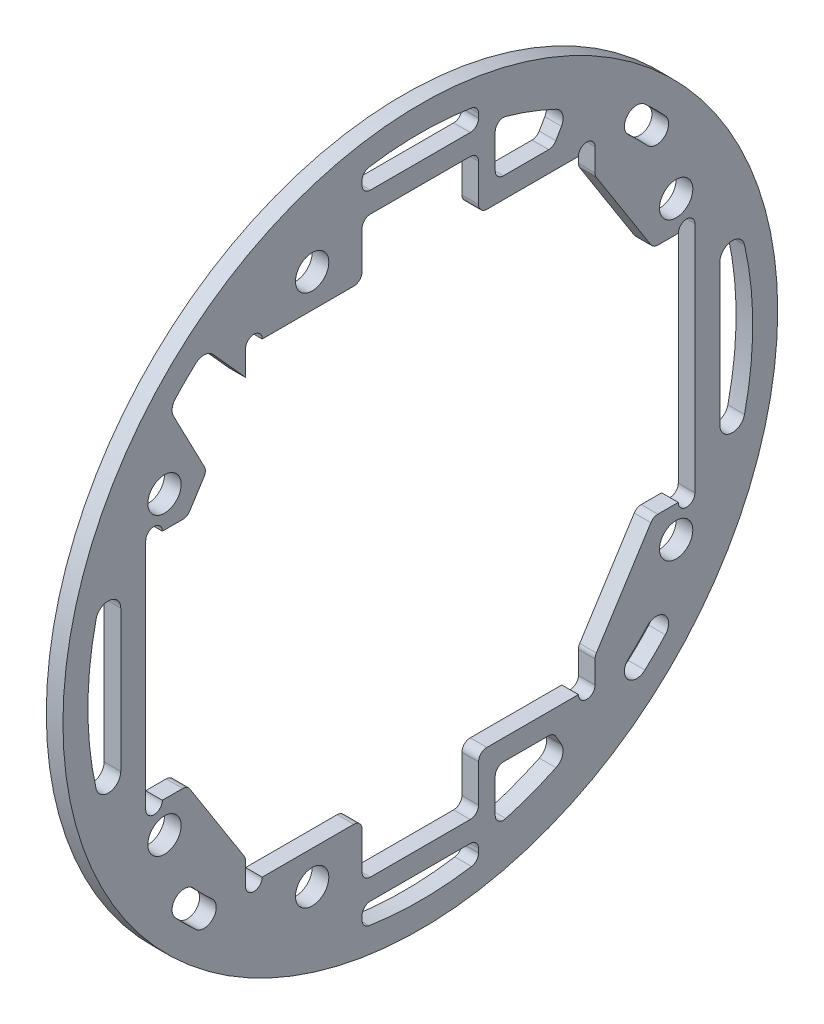
SolidWorks part; units mm, degrees
material "Thornel Mat VMA"
ref_plane "前视基准面" through (0, 0, 0) normal (0, 0, 1) x (1, 0, 0)
ref_plane "上视基准面" through (0, 0, 0) normal (0, 1, 0) x (1, 0, 0)
ref_plane "右视基准面" through (0, 0, 0) normal (1, 0, 0) x (0, 0, -1)
sketch "草图1" plane through (0, 0, 0) normal (1, 0, 0) x (0, 0, -1)
  line L25 (-21, 28) -> (21, 28)
  line L26 (-28, 14) -> (-33, 14)
  line L31 (-33, 14) -> (-33, -14)
  line L38 (1.1, 0) -> (-1.1, 0) construction
  line L48 (0, 1.1) -> (0, -1.1) construction
  line L58 (-21, 25) -> (-21, 28)
  line L79 (21, 25) -> (21, 28)
  line L81 (33, 14) -> (33, -14)
  line L82 (28, 14) -> (33, 14)
  line L83 (28, -14) -> (33, -14)
  line L84 (-21, -25) -> (-21, -28)
  line L85 (-28, -14) -> (-33, -14)
  line L86 (-21, -28) -> (21, -28)
  line L87 (21, -25) -> (21, -28)
  line L88 (-30.7439, 17.75) -> (0, 0) construction
  line L89 (0, 0) -> (-30.7439, -17.75) construction
  line L90 (-28, 14) -> (-21, 25)
  line L91 (-28, -14) -> (-21, -25)
  line L92 (28, -14) -> (21, -25)
  line L93 (28, 14) -> (21, 25)
  circle A8 centre (0, 0) radius 42.95
  circle A9 centre (-30.7439, 17.75) radius 2
  circle A11 centre (-30.7439, -17.75) radius 2
  circle A12 centre (30.7439, -17.75) radius 2
  circle A13 centre (30.7439, 17.75) radius 2
  circle A14 centre (0, 0) radius 35.5 construction
  dimension "D3" = 56
  dimension "D4" = 66
  dimension "D8" = 60
  dimension "D9" = 3
  dimension "D10" = 85.9
  dimension "D11" = 5
  dimension "D7" = 4
  dimension "D6" = 71
  dimension "D2" = 42
  dimension "D5" = 28
extrude "凸台-拉伸1" add sketch "草图1" along normal blind 2
sketch "草图5" plane through (2, 0, 0) normal (1, 0, 0) x (0, 0, -1)
  line L30 (21, 28) -> (-21, 28) construction
  line L31 (-21, 28) -> (-21, 25) construction
  line L50 (-28, 14) -> (-33, 14) construction
  line L52 (-36, 8.4943) -> (-36, -8.4943)
  line L55 (-33, 14) -> (-33, -14) construction
  line L56 (1.1, 0) -> (-1.1, 0) construction
  line L58 (0, 1.1) -> (0, -1.1) construction
  line L60 (-7, 34.5) -> (7, 34.5)
  line L69 (-7, 39.332) -> (-7, 37)
  line L70 (-7, 37) -> (7, 37)
  line L71 (7, 39.332) -> (7, 37)
  line L72 (9, 30.5) -> (9, 36.8674)
  line L73 (36, 8.4943) -> (36, -8.4943)
  line L87 (-7, 34.5) -> (-7, 28)
  line L91 (16.9606, 32.1638) -> (16, 30.5)
  line L92 (16, 30.5) -> (9, 30.5)
  line L93 (7, 34.5) -> (7, 28)
  line L94 (-7, 28) -> (7, 28)
  line L96 (-7, -28) -> (7, -28)
  line L97 (7, -34.5) -> (7, -28)
  line L98 (16, -30.5) -> (9, -30.5)
  line L99 (16.9606, -32.1638) -> (16, -30.5)
  line L101 (-7, -34.5) -> (-7, -28)
  line L103 (9, -30.5) -> (9, -36.8674)
  line L104 (7, -39.332) -> (7, -37)
  line L105 (-7, -37) -> (7, -37)
  line L106 (-7, -39.332) -> (-7, -37)
  line L108 (-7, -34.5) -> (7, -34.5)
  arc A0 (-28.3606, 26) -> (-26, 28.3606) centre (0, 0) cw construction
  arc A1 (-26.9968, 29.4479) -> (-29.4479, 26.9968) centre (0, 0) ccw
  arc A2 (-25.0032, 27.2734) -> (-27.2734, 25.0032) centre (0, 0) ccw
  arc A4 (-25.0032, 27.2734) -> (-26.9968, 29.4479) centre (-26, 28.3606) ccw
  arc A5 (-29.4479, 26.9968) -> (-27.2734, 25.0032) centre (-28.3606, 26) ccw
  arc A6 (-36, 8.4943) -> (-38.9629, 8.8256) centre (-37.5, 8.4943) ccw
  circle A7 centre (0, 0) radius 42.95 construction
  arc A8 (7, 39.332) -> (-7, 39.332) centre (0, 0) ccw
  arc A11 (-38.9629, 8.8256) -> (-38.9629, -8.8256) centre (0, 0) ccw
  arc A12 (-38.9629, -8.8256) -> (-36, -8.4943) centre (-37.5, -8.4943) ccw
  arc A13 (9, 36.8674) -> (16.3061, 34.2683) centre (0, 0) cw
  circle A24 centre (32, 14) radius 1
  circle A29 centre (20, 28) radius 1
  circle A34 centre (-20, 28) radius 1
  circle A35 centre (-32, 14) radius 1
  arc A44 (38.9629, 8.8256) -> (38.9629, -8.8256) centre (0, 0) cw
  arc A45 (16.9606, 32.1638) -> (16.3061, 34.2683) centre (15.6616, 32.9138) ccw
  arc A46 (36, 8.4943) -> (38.9629, 8.8256) centre (37.5, 8.4943) cw
  arc A47 (28.3606, 26) -> (26, 28.3606) centre (0, 0) ccw construction
  arc A48 (26.9968, 29.4479) -> (29.4479, 26.9968) centre (0, 0) cw
  arc A49 (25.0032, 27.2734) -> (27.2734, 25.0032) centre (0, 0) cw
  arc A50 (25.0032, 27.2734) -> (26.9968, 29.4479) centre (26, 28.3606) cw
  arc A51 (29.4479, 26.9968) -> (27.2734, 25.0032) centre (28.3606, 26) cw
  arc A52 (36, -8.4943) -> (38.9629, -8.8256) centre (37.5, -8.4943) ccw
  circle A55 centre (-32, -14) radius 1
  circle A56 centre (-20, -28) radius 1
  circle A57 centre (20, -28) radius 1
  circle A58 centre (32, -14) radius 1
  arc A62 (28.3606, -26) -> (26, -28.3606) centre (0, 0) cw construction
  arc A63 (26.9968, -29.4479) -> (29.4479, -26.9968) centre (0, 0) ccw
  arc A64 (25.0032, -27.2734) -> (27.2734, -25.0032) centre (0, 0) ccw
  arc A65 (25.0032, -27.2734) -> (26.9968, -29.4479) centre (26, -28.3606) ccw
  arc A66 (29.4479, -26.9968) -> (27.2734, -25.0032) centre (28.3606, -26) ccw
  arc A67 (-28.3606, -26) -> (-26, -28.3606) centre (0, 0) ccw construction
  arc A68 (-26.9968, -29.4479) -> (-29.4479, -26.9968) centre (0, 0) cw
  arc A69 (-25.0032, -27.2734) -> (-27.2734, -25.0032) centre (0, 0) cw
  arc A70 (-25.0032, -27.2734) -> (-26.9968, -29.4479) centre (-26, -28.3606) cw
  arc A71 (-29.4479, -26.9968) -> (-27.2734, -25.0032) centre (-28.3606, -26) cw
  arc A74 (16.9606, -32.1638) -> (16.3061, -34.2683) centre (15.6616, -32.9138) cw
  arc A75 (9, -36.8674) -> (16.3061, -34.2683) centre (0, 0) ccw
  arc A76 (7, -39.332) -> (-7, -39.332) centre (0, 0) cw
  circle A78 centre (-13, 32) radius 2
  circle A79 centre (-13, -32) radius 2
  point P3 (-27.2059, 27.2059)
  point P50 (27.2059, 27.2059)
  point P94 (27.2059, -27.2059)
  point P110 (-27.2059, -27.2059)
  dimension "D8" = 3
  dimension "D1" = 37
  dimension "D2" = 3
  dimension "D3" = 2
  dimension "D5" = 120
  dimension "D6" = 5
  dimension "D7" = 12
  dimension "D9" = 1.5
  dimension "D10" = 2
  dimension "D12" = 7
  dimension "D11" = 2
  dimension "D15" = 1.5
  dimension "D17" = 4
  dimension "D18" = 4
  dimension "D19" = 6
  dimension "D4" = 14
  dimension "D13" = 6.5
  dimension "D14" = 2.5
  dimension "D16" = 2.5
extrude "切除-拉伸2" cut sketch "草图5" against normal through all
sketch "草图6" plane through (2, 0, 0) normal (1, 0, 0) x (0, 0, -1)
  line L0 (-29.6686, 25.3183) -> (-25.6743, 17.6547)
  line L2 (-24.9025, 29.3461) -> (-21, 25)
  line L3 (-29.6686, 25.3183) -> (-24.9025, 29.3461)
  line L4 (-25.6743, 17.6547) -> (-21, 25)
  line L5 (-21, 25) -> (-28, 14) construction
  arc A2 (-25.0032, 27.2734) -> (-26.9968, 29.4479) centre (-26, 28.3606) ccw construction
  arc A3 (-29.4479, 26.9968) -> (-27.2734, 25.0032) centre (-28.3606, 26) ccw construction
  dimension "D1" = 60
extrude "切除-拉伸3" cut sketch "草图6" against normal through all
fillet "圆角1" radius 1 30 edges at (1, 28, 7) (1, 34.5, -7) (1, 28, -7) (1, 25, -21) (1, 14, -28) (1, -14, -28) (1, -25, -21) (1, -28, -7) (1, -34.5, -7) (1, -34.5, 7) (1, -28, 7) (1, -25, 21) (1, -14, 28) (1, 14, 28) (1, 17.6547, 25.6743) (1, 37, -7) (1, 37, 7) (1, 39.332, 7) (1, 39.332, -7) (1, 36.8674, -9) (1, 30.5, -16) (1, 30.5, -9) (1, -37, 7) (1, -37, -7) (1, -39.332, -7) (1, -39.332, 7) (1, -36.8674, -9) (1, -30.5, -9) (1, -30.5, -16) (1, 34.5, 7)
